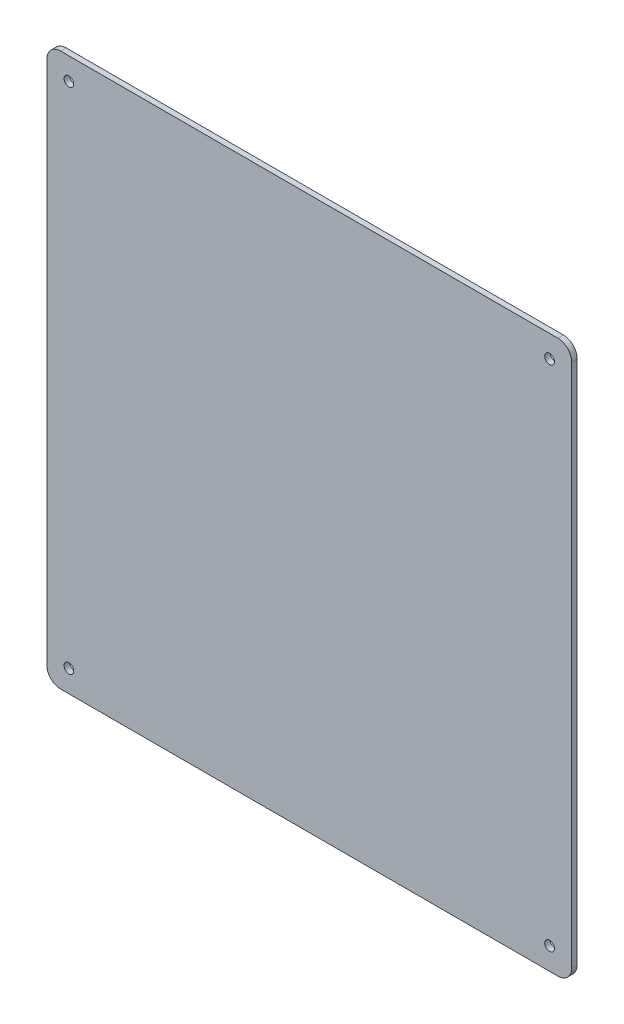
SolidWorks part; units mm, degrees
material "S30403 GB/T3280-2015"
ref_plane "Front" through (0, 0, 0) normal (0, 0, 1) x (1, 0, 0)
ref_plane "Top" through (0, 0, 0) normal (0, 1, 0) x (1, 0, 0)
ref_plane "Right" through (0, 0, 0) normal (1, 0, 0) x (0, 0, -1)
sketch "草图1" plane through (0, 0, 0) normal (0, 0, 1) x (1, 0, 0)
  line L1 (-133.6121, 74.3506) -> (56.3879, 74.3506)
  line L2 (-133.6121, 74.3506) -> (-133.6121, -125.6494)
  line L3 (-133.6121, -125.6494) -> (56.3879, -125.6494)
  line L4 (56.3879, 74.3506) -> (56.3879, -125.6494)
  dimension "D1" = 200
  dimension "D2" = 190
extrude "凸台-拉伸1" add sketch "草图1" along normal blind 2
sketch "草图2" plane through (0, 0, 2) normal (0, 0, 1) x (1, 0, 0)
  line L0 (56.3879, 74.3506) -> (-133.6121, 74.3506) construction
  line L1 (-133.6121, -125.6494) -> (56.3879, -125.6494) construction
  line L2 (-133.6121, 74.3506) -> (-133.6121, -125.6494) construction
  line L3 (56.3879, -125.6494) -> (56.3879, 74.3506) construction
  circle A0 centre (-125.6121, 66.3506) radius 1.75
  circle A1 centre (48.3879, 66.3506) radius 1.75
  circle A2 centre (-125.6121, -117.6494) radius 1.75
  circle A3 centre (48.3879, -117.6494) radius 1.75
  dimension "D4" = 3.5
  dimension "D5" = 3.5
  dimension "D6" = 3.5
  dimension "D7" = 3.5
  dimension "D11" = 8
  dimension "D1" = 8
  dimension "D2" = 8
  dimension "D3" = 8
  dimension "D8" = 8
  dimension "D9" = 8
  dimension "D10" = 8
  dimension "D12" = 8
extrude "切除-拉伸1" cut sketch "草图2" against normal through all
fillet "圆角1" radius 5 4 edges at (56.3879, 74.3506, 1) (56.3879, -125.6494, 1) (-133.6121, -125.6494, 1) (-133.6121, 74.3506, 1)
